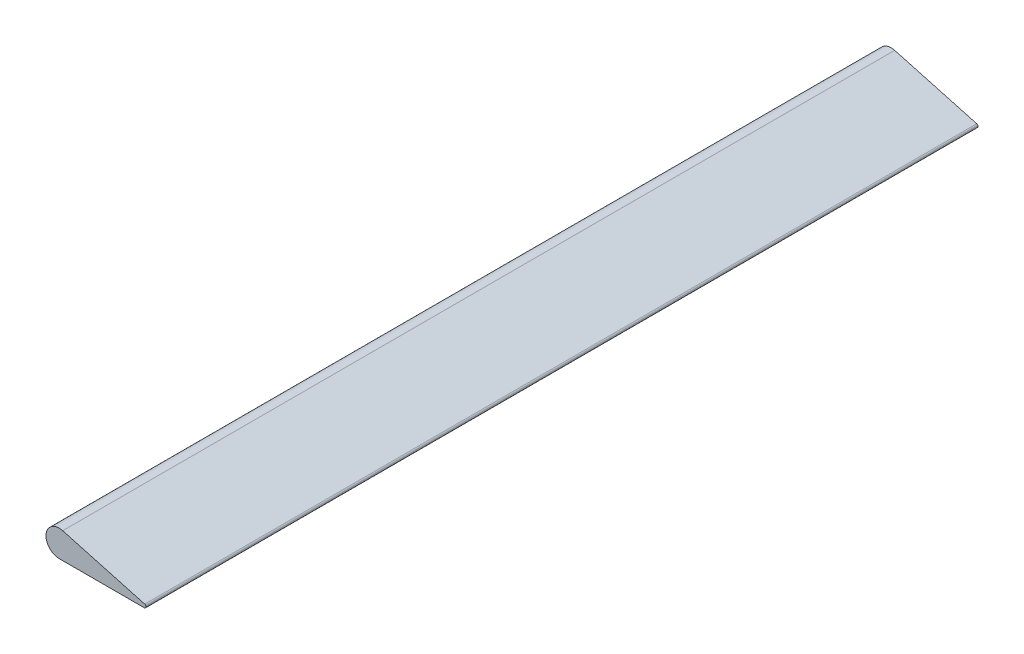
SolidWorks part; units mm, degrees
material "ABS"
ref_plane "Front Plane" through (0, 0, 0) normal (0, 0, 1) x (1, 0, 0)
ref_plane "Top Plane" through (0, 0, 0) normal (0, 1, 0) x (1, 0, 0)
ref_plane "Right Plane" through (0, 0, 0) normal (1, 0, 0) x (0, 0, -1)
sketch "Sketch2" plane through (0, 0, -3) normal (0, 0, 1) x (1, 0, 0)
  line L0 (442.7178, 24.3712) -> (474.4331, 20.1125) construction
  line L1 (442.557, 28.8563) -> (474.4331, 20.1125) construction
  line L4 (446.392, 20.1125) -> (474.4331, 20.1125)
  line L5 (474.4331, 20.1125) -> (447.3909, 27.5303)
  line L6 (474.4331, 20.1125) -> (441.3938, 20.1125) construction
  arc A1 (447.3909, 27.5303) -> (446.392, 20.1125) centre (446.392, 23.8886) ccw
extrude "Boss-Extrude1" add sketch "Sketch2" along normal blind 238
sketch "Sketch3" plane through (0, -30.5897, 0) normal (0, -1, 0) x (1, 0, 0)
  line L0 (442.6158, 235) -> (442.6158, -3) construction
  line L1 (442.6158, 190) -> (457.6158, 190)
  line L2 (442.6158, 190) -> (442.6158, 175)
  line L3 (442.6158, 175) -> (457.6158, 175)
  line L4 (457.6158, 190) -> (457.6158, 175)
  line L5 (446.392, -3) -> (474.4331, -3) construction
  line L6 (442.6158, 42) -> (457.6158, 42)
  line L7 (442.6158, 42) -> (442.6158, 57)
  line L8 (442.6158, 57) -> (457.6158, 57)
  line L9 (457.6158, 42) -> (457.6158, 57)
  line L10 (446.392, 235) -> (474.4331, 235) construction
  dimension "D1" = 15
  dimension "D2" = 15
  dimension "D3" = 45
  dimension "D4" = 15
  dimension "D5" = 15
  dimension "D6" = 45
extrude "Cut-Extrude1" cut sketch "Sketch3" against normal blind 54
fillet "Fillet1" radius 0.5 1 edges at (474.4331, 20.1125, 116)
